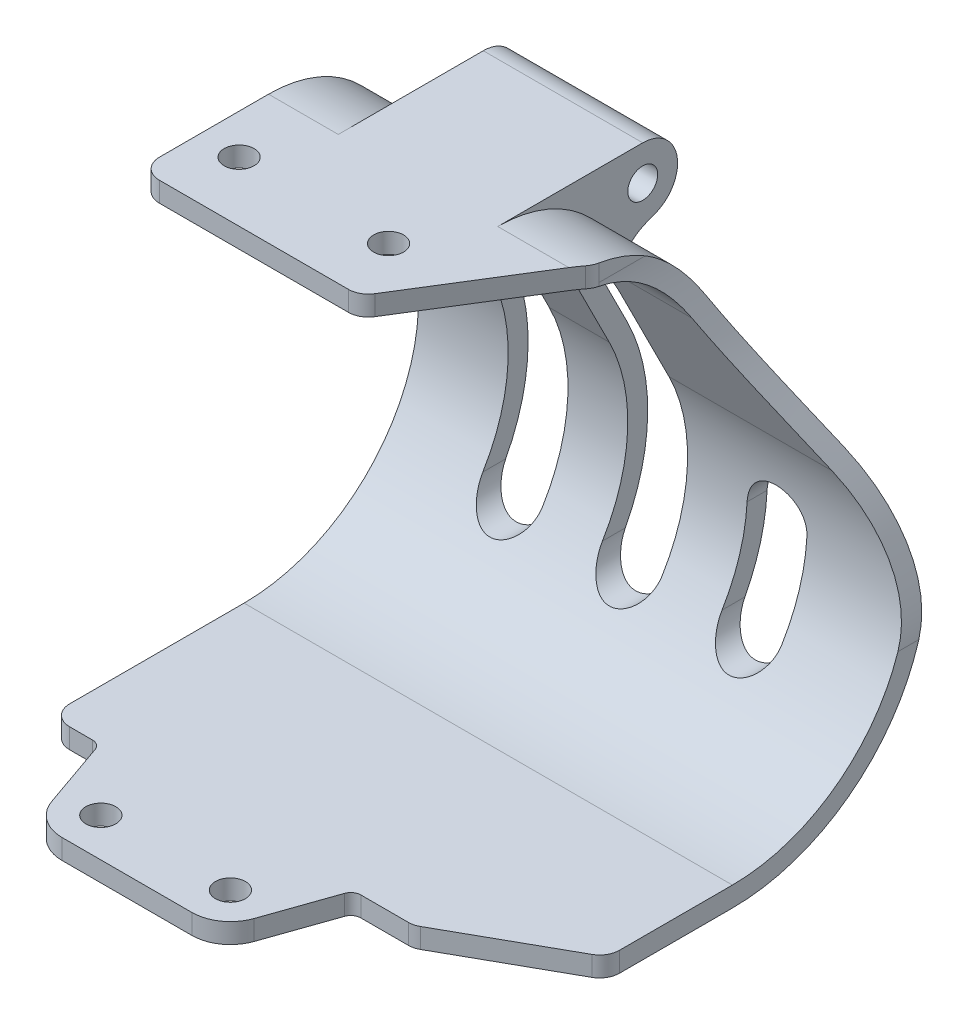
SolidWorks part; units mm, degrees
ref_plane "Front Plane" through (0, 0, 0) normal (0, 0, 1) x (1, 0, 0)
ref_plane "Top Plane" through (0, 0, 0) normal (0, 1, 0) x (1, 0, 0)
ref_plane "Right Plane" through (0, 0, 0) normal (1, 0, 0) x (0, 0, -1)
sketch "Sketch3" plane through (0, 0, 0) normal (1, 0, 0) x (0, 0, -1)
  line L0 (-26.9848, -23.0394) -> (2.5152, -23.0394)
  line L1 (-10.9848, 22.9606) -> (1.9674, 22.9606)
  line L2 (19.0402, 3.7776) -> (12.7204, 16.3344)
  line L3 (21.0152, -4.5394) -> (21.0152, 13.8904) construction
  line L4 (-10.9848, 21.9606) -> (1.9674, 21.9606)
  line L5 (18.147, 3.328) -> (11.8272, 15.8848)
  line L6 (-26.9848, -22.0394) -> (2.5152, -22.0394)
  line L7 (-10.9848, 23.9606) -> (1.9674, 23.9606)
  line L8 (19.9335, 4.2271) -> (13.6137, 16.784)
  line L9 (-26.9848, -24.0394) -> (2.5152, -24.0394)
  line L10 (-10.9848, 23.9606) -> (-10.9848, 21.9606)
  line L11 (-26.9848, -22.0394) -> (-26.9848, -24.0394)
  arc A0 (2.5152, -23.0394) -> (19.0402, 3.7776) centre (2.5152, -4.5394) ccw
  arc A1 (1.9674, 22.9606) -> (12.7204, 16.3344) centre (1.9674, 10.9225) cw
  arc A2 (1.9674, 21.9606) -> (11.8272, 15.8848) centre (1.9674, 10.9225) cw
  arc A3 (2.5152, -22.0394) -> (18.147, 3.328) centre (2.5152, -4.5394) ccw
  arc A4 (1.9674, 23.9606) -> (13.6137, 16.784) centre (1.9674, 10.9225) cw
  arc A5 (2.5152, -24.0394) -> (19.9335, 4.2271) centre (2.5152, -4.5394) ccw
  dimension "D4" = 18.5
  dimension "D1" = 48
  dimension "D2" = 46
  dimension "D3" = 63.284
  dimension "D5" = 32
  dimension "D6" = 1
  dimension "D7" = 1
extrude "Boss-Extrude2" add sketch "Sketch3" along normal blind 49 separate body contours A0 L3 A5 L8 A4 L7 L10 L1 A1 L2 | A3 L6 L11 L0 A0 L2 A1 L1 L10 L4 A2 L5 | L3 A0 L0 L11 L9 A5
sketch "Sketch5" plane through (0, -24.0394, 0) normal (0, -1, 0) x (1, 0, 0)
  line L0 (0, 12.2348) -> (0, 14.9848)
  line L1 (0, 26.9848) -> (0, -2.5152) construction
  line L2 (2, 16.9848) -> (4.2905, 16.9848)
  line L3 (5.2344, 17.6545) -> (7.5915, 24.3892)
  line L4 (49, 26.9848) -> (0, 26.9848) construction
  line L5 (11.25, 26.9848) -> (24.25, 26.9848)
  line L6 (27.9085, 24.3892) -> (30.2656, 17.6545)
  line L7 (31.2095, 16.9848) -> (35.9781, 16.9848)
  line L8 (36.9553, 16.7298) -> (47.9772, 10.5576)
  line L9 (49, 26.9848) -> (49, -2.5152) construction
  line L10 (5, 16.9848) -> (30.5, 16.9848) construction
  line L11 (17.75, 26.9848) -> (17.75, 16.9848) construction
  line L12 (49, 8.8126) -> (49, 4.8655)
  line L13 (0, 14.9848) -> (0, 26.9848)
  line L14 (0, 26.9848) -> (11.25, 26.9848)
  line L15 (24.25, 26.9848) -> (49, 26.9848)
  line L16 (49, 26.9848) -> (49, 8.8126)
  arc A0 (49, 8.8126) -> (47.9772, 10.5576) centre (47, 8.8126) ccw
  arc A1 (36.9553, 16.7298) -> (35.9781, 16.9848) centre (35.9781, 14.9848) ccw
  arc A2 (2, 16.9848) -> (0, 14.9848) centre (2, 14.9848) ccw
  arc A3 (30.2656, 17.6545) -> (31.2095, 16.9848) centre (31.2095, 17.9848) ccw
  arc A4 (5.2344, 17.6545) -> (4.2905, 16.9848) centre (4.2905, 17.9848) cw
  arc A5 (27.9085, 24.3892) -> (24.25, 26.9848) centre (24.25, 23.1087) ccw
  arc A6 (11.25, 26.9848) -> (7.5915, 24.3892) centre (11.25, 23.1087) ccw
  circle A7 centre (11.25, 23.1087) radius 1.5
  circle A8 centre (24.25, 23.1087) radius 1.5
  point P19 (49, 9.9848)
  point P22 (36.5, 16.9848)
  point P25 (0, 16.9848)
  point P34 (27, 26.9848)
  point P37 (8.5, 26.9848)
  line M6 (0, 26.9848) -> (0, -2.5152)
  line M8 (49, -2.5152) -> (49, 26.9848)
  line M9 (49, 26.9848) -> (0, 26.9848)
  dimension "D7" = 2
  dimension "D8" = 1
  dimension "D9" = 13
  dimension "D10" = 3
  dimension "D11" = 3
  dimension "D1" = 5
  dimension "D2" = 10
  dimension "D3" = 18.5
  dimension "D4" = 30.5
  dimension "D5" = 6
  dimension "D6" = 17
extrude "Cut-Extrude1" cut sketch "Sketch5" against normal up to surface (2 mm away) contours A6 A2 L2 A4 L3 M9 M6 | A7 | A8 | A5 L6 A3 L7 A1 L8 A0 M8 M9 up to face at (24.5, -22.0394, 12.2348)
ref_plane "Plane3" through (10, 0, 0) normal (-1, 0, 0) x (0, 0, 1)
sketch "Sketch10" plane through (10, 0, 0) normal (-1, 0, 0) x (0, 0, 1)
  line L0 (-1.9674, 23.9606) -> (-16.5152, 23.9606)
  line L1 (10.9848, 23.9606) -> (10.9848, 21.9606) construction
  line L2 (-16.5152, 21.9606) -> (-12.4117, 21.9606) construction
  line L3 (-19.9335, 4.2271) -> (-13.6137, 16.784) construction
  line L6 (-19.9335, 4.2271) -> (-13.6137, 16.784)
  line L7 (-19.9335, 4.2271) -> (-13.6137, 16.784)
  arc A0 (-16.5152, 23.9606) -> (-17.6489, 17.1493) centre (-16.5152, 20.4606) ccw
  circle A1 centre (-16.5152, 20.4606) radius 1.5
  arc A5 (-1.9674, 23.9606) -> (-13.6137, 16.784) centre (-1.9674, 10.9225) ccw
  arc A6 (-1.9674, 23.9606) -> (-13.6137, 16.784) centre (-1.9674, 10.9225) ccw
  spline S0 degree 3 poles (-17.6489, 17.1493) (-16.2762, 16.6793) (-15.0724, 16.0474) (-14.653, 14.7189) knots 0 0 0 0 1 1 1 1
  point P11 (-14.653, 14.7189)
  point P17 (-17.6489, 17.1493)
  point P18 (0, 0)
  dimension "D1" = 27.5
  dimension "D2" = 3
  dimension "D3" = 2
  dimension "D4" = 0
extrude "Boss-Extrude5" add sketch "Sketch10" against normal blind 16
sketch "Sketch7" plane through (0, 0, 0) normal (0, 0, 1) x (1, 0, 0)
  line L0 (12, 13.2854) -> (12, -13.6261) construction
  line L1 (15, 13.2854) -> (15, -13.6261)
  line L2 (9, 13.2854) -> (9, -13.6261)
  line L3 (24, 13.2854) -> (24, -13.6261) construction
  line L4 (27, 13.2854) -> (27, -13.6261)
  line L5 (21, 13.2854) -> (21, -13.6261)
  line L6 (36, -13.6261) -> (36, -5.4735) construction
  line L7 (33, -13.6261) -> (33, -5.4735)
  line L8 (39, -13.6261) -> (39, -5.4735)
  line L9 (36, -13.6261) -> (12, -13.6261) construction
  line L10 (12, 13.2854) -> (24, 13.2854) construction
  line L11 (0, 11.6724) -> (0, 13.3843)
  line L12 (0.75, 14.1343) -> (2.25, 14.1343)
  line L13 (3, 14.8843) -> (3, 23.9606)
  line L14 (3, 23.9606) -> (7.6786, 23.9606)
  line L15 (49, -12.862) -> (49, -10.0605)
  line L16 (34.0807, 23.9606) -> (34.0807, 22.0929)
  line L17 (49, -24.0394) -> (49, 4.2271) construction
  line L18 (49, 23.9606) -> (26, 23.9606) construction
  line L19 (49, -10.0605) -> (49, 23.9606)
  line L20 (34.0807, 23.9606) -> (49, 23.9606)
  line L21 (3, 23.9606) -> (0, 23.9606)
  line L22 (0, 13.3843) -> (0, 23.9606)
  arc A0 (15, 13.2854) -> (9, 13.2854) centre (12, 13.2854) ccw
  arc A1 (9, -13.6261) -> (15, -13.6261) centre (12, -13.6261) ccw
  arc A2 (27, 13.2854) -> (21, 13.2854) centre (24, 13.2854) ccw
  arc A3 (21, -13.6261) -> (27, -13.6261) centre (24, -13.6261) ccw
  arc A4 (33, -13.6261) -> (39, -13.6261) centre (36, -13.6261) ccw
  arc A5 (39, -5.4735) -> (33, -5.4735) centre (36, -5.4735) ccw
  arc A6 (3, 14.8843) -> (2.25, 14.1343) centre (2.25, 14.8843) cw
  arc A7 (0.75, 14.1343) -> (0, 13.3843) centre (0.75, 13.3843) ccw
  spline S0 degree 3 poles (34.0807, 22.0929) (34.0807, 12.0903) (49, 0.0404) (49, -10.0605) knots 0 0 0 0 1 1 1 1
  point P2 (12, -0.1704)
  point P7 (24, -0.1704)
  point P14 (36, -9.5498)
  point P37 (0.3202, 23.9606)
  dimension "D6" = 0.75
  dimension "D1" = 6
  dimension "D2" = 6
  dimension "D3" = 6
  dimension "D4" = 9
  dimension "D5" = 39
  dimension "D7" = 3
extrude "Cut-Extrude3" cut sketch "Sketch7" against normal through all and the other way through all contours L16 S0 L19 L20 | L8 A5 L7 A4 | L5 A3 L4 A2 | L2 A1 L1 A0 | A7 L12 A6 L13 L21 L22
sketch "Sketch11" plane through (0, 23.9606, 0) normal (0, 1, 0) x (1, 0, 0)
  line L0 (3, -5.6088) -> (3, -8.9848)
  line L1 (3, 1.9674) -> (3, -10.9848) construction
  line L2 (5, -10.9848) -> (7.7062, -10.9848)
  line L3 (34.0807, -10.9848) -> (3, -10.9848) construction
  line L4 (34.0807, 6.2236) -> (34.0807, 4.0589)
  line L5 (34.0807, 1.9674) -> (34.0807, 8.6915) construction
  line L6 (33.7791, 3.0027) -> (25.6676, -10.041)
  line L7 (23.9692, -10.9848) -> (21.9324, -10.9848)
  line L8 (34.0807, 1.9674) -> (34.0807, -10.9848) construction
  line L9 (3, -8.9848) -> (3, -10.9848)
  line L10 (3, -10.9848) -> (5, -10.9848)
  line L11 (23.9692, -10.9848) -> (34.0807, -10.9848)
  line L13 (5.5, -4.9848) -> (5.5, -1.5072) construction
  line L14 (7, -6.4848) -> (22, -6.4848) construction
  line L15 (8.5, -4.9848) -> (8.5, -1.9318) construction
  line L16 (20.5, -4.9848) -> (20.5, -0.3552) construction
  line L17 (34.0807, 4.0589) -> (35.2204, 4.0589)
  line L18 (35.2204, 4.0589) -> (35.2204, -10.9848)
  line L19 (35.2204, -10.9848) -> (34.0807, -10.9848)
  arc A0 (34.0807, 4.0589) -> (33.7791, 3.0027) centre (32.0807, 4.0589) cw
  arc A1 (25.6676, -10.041) -> (23.9692, -10.9848) centre (23.9692, -8.9848) cw
  arc A2 (5, -10.9848) -> (3, -8.9848) centre (5, -8.9848) cw
  circle A3 centre (7, -4.9848) radius 1.5
  circle A4 centre (22, -4.9848) radius 1.5
  point P19 (34.0807, 3.4877)
  point P22 (25.0807, -10.9848)
  point P25 (3, -10.9848)
  point P42 (33.7791, -10.9848)
  dimension "D2" = 2
  dimension "D3" = 3
  dimension "D4" = 3
  dimension "D1" = 9
  dimension "D5" = 4.5
  dimension "D6" = 2.5
  dimension "D7" = 12
extrude "Cut-Extrude4" cut sketch "Sketch11" against normal blind 10
